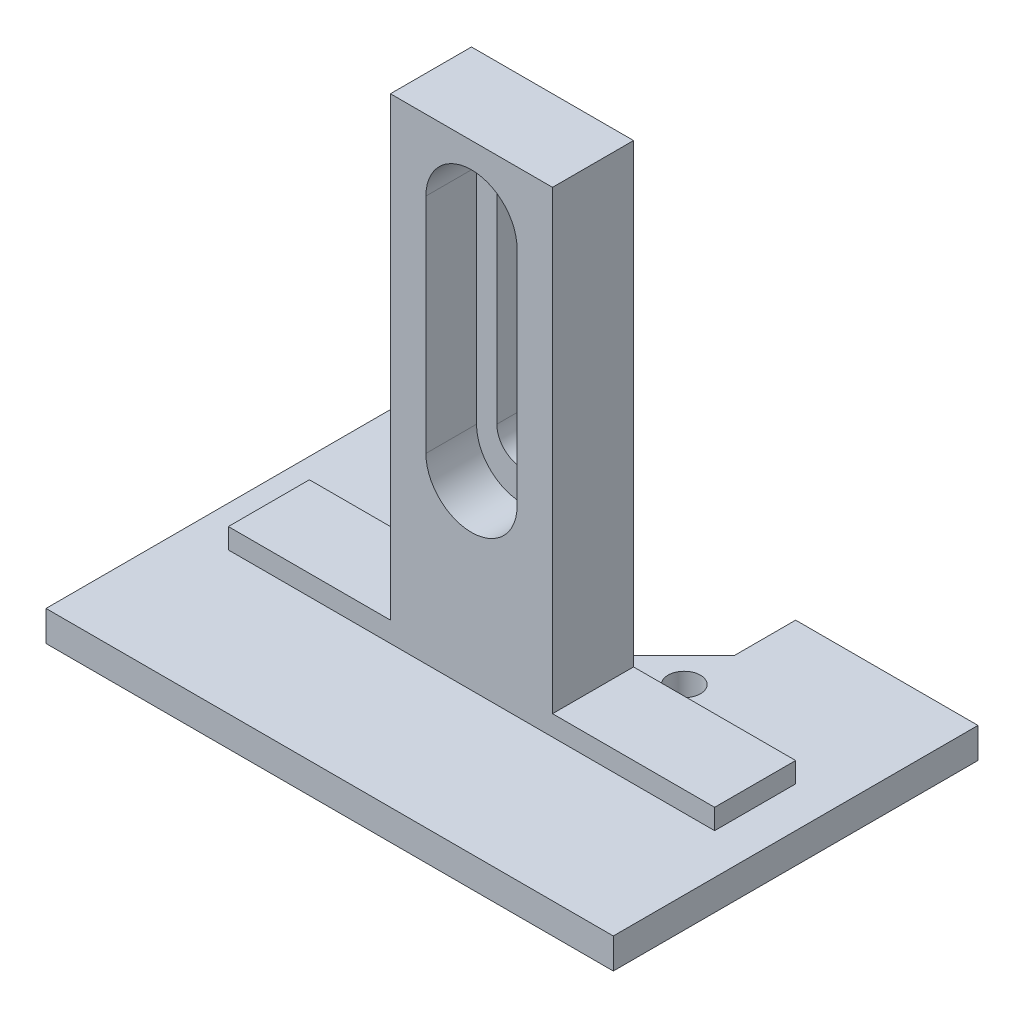
SolidWorks part; units mm, degrees
ref_plane "前视基准面" through (0, 0, 0) normal (0, 0, 1) x (1, 0, 0)
ref_plane "上视基准面" through (0, 0, 0) normal (0, 1, 0) x (1, 0, 0)
ref_plane "右视基准面" through (0, 0, 0) normal (1, 0, 0) x (0, 0, -1)
sketch "草图2" plane through (0, 0, 0) normal (0, 1, 0) x (1, 0, 0)
  line L1 (-28, 36) -> (-10, 36)
  line L2 (-28, 36) -> (-28, 0)
  line L3 (-28, 0) -> (28, 0)
  line L4 (28, 36) -> (28, 0)
  line L5 (0, 26) -> (0, 0) construction
  line L7 (-10, 23.4) -> (-4.4595, 23.4) construction
  line L8 (-10, 29.9497) -> (-3.4503, 23.4)
  line L9 (-10, 25) -> (-7.5251, 27.4749) construction
  line L10 (10, 29.9497) -> (3.4503, 23.4)
  line L11 (-3.4503, 23.4) -> (3.4503, 23.4)
  line L12 (10, 36) -> (28, 36)
  line L13 (-10, 36) -> (-10, 29.9497)
  line L15 (10, 36) -> (10, 29.9497)
  circle A0 centre (-10, 25) radius 1.6
  circle A1 centre (10, 25) radius 1.6
  circle A2 centre (-10, 25) radius 3.5 construction
  dimension "D2" = 3.2
  dimension "D4" = 56
  dimension "D5" = 45
  dimension "D6" = 7
  dimension "D1" = 20
  dimension "D3" = 11
  dimension "D7" = 36
  dimension "D8" = 20
extrude "凸台-拉伸2" add sketch "草图2" against normal blind 3
sketch "草图3" plane through (0, 0, 0) normal (0, 1, 0) x (1, 0, 0)
  line L0 (28, 0) -> (28, 36) construction
  line L1 (-24, 14) -> (24, 14)
  line L2 (-24, 14) -> (-24, 22)
  line L3 (-24, 22) -> (24, 22)
  line L4 (24, 14) -> (24, 22)
  line L5 (0, 14) -> (0, 0) construction
  line L6 (-28, 36) -> (-28, 0) construction
  line L8 (-35.2, 18) -> (28, 18) construction
  point P17 (24, 18)
  dimension "D1" = 4
  dimension "D2" = 8
extrude "凸台-拉伸3" add sketch "草图3" along normal blind 2
sketch "草图4" plane through (0, 2, 0) normal (0, 1, 0) x (1, 0, 0)
  line L0 (-24, 14) -> (24, 14) construction
  line L1 (-8, 14) -> (8, 14)
  line L2 (-8, 14) -> (-8, 22)
  line L3 (-8, 22) -> (8, 22)
  line L4 (8, 14) -> (8, 22)
  line L6 (0, 14) -> (0, 0) construction
  line L7 (24, 22) -> (-24, 22) construction
  dimension "D1" = 16
extrude "凸台-拉伸4" add sketch "草图4" along normal blind 45
sketch "草图5" plane through (0, 0, -14) normal (0, 0, 1) x (1, 0, 0)
  line L0 (0, 39) -> (0, 19) construction
  line L1 (2.5, 39) -> (2.5, 19)
  line L2 (-2.5, 39) -> (-2.5, 19)
  line L3 (-8, 47) -> (8, 47) construction
  arc A0 (2.5, 39) -> (-2.5, 39) centre (0, 39) ccw
  arc A1 (-2.5, 19) -> (2.5, 19) centre (0, 19) ccw
  point P2 (0, 29)
  point P9 (0, 47)
  dimension "D1" = 8
  dimension "D2" = 20
  dimension "D3" = 5
extrude "切除-拉伸1" cut sketch "草图5" against normal through all
sketch "草图6" plane through (0, 0, -14) normal (0, 0, 1) x (1, 0, 0)
  line L0 (0, 40) -> (0, 18) construction
  line L1 (4.5, 40) -> (4.5, 18)
  line L2 (-4.5, 40) -> (-4.5, 18)
  line L3 (-8, 47) -> (8, 47) construction
  line L4 (0, 44.5) -> (17.2983, 44.5) construction
  line L5 (12.2767, 41.5) -> (19.6745, 41.5) construction
  line L6 (0, 13.5) -> (19.6745, 13.5) construction
  line L7 (11.0213, 16.5) -> (19.3158, 16.5) construction
  arc A0 (2.5, 39) -> (-2.5, 39) centre (0, 39) ccw construction
  arc A1 (-2.5, 19) -> (2.5, 19) centre (0, 19) ccw construction
  arc A2 (4.5, 40) -> (-4.5, 40) centre (0, 40) ccw
  arc A3 (-4.5, 18) -> (4.5, 18) centre (0, 18) ccw
  point P5 (0, 47)
  point P8 (0, 29)
  dimension "D1" = 9
  dimension "D2" = 3
  dimension "D3" = 3
extrude "切除-拉伸2" cut sketch "草图6" against normal offset from surface (5 mm away) 3 up to face at (0, 29, -22)
